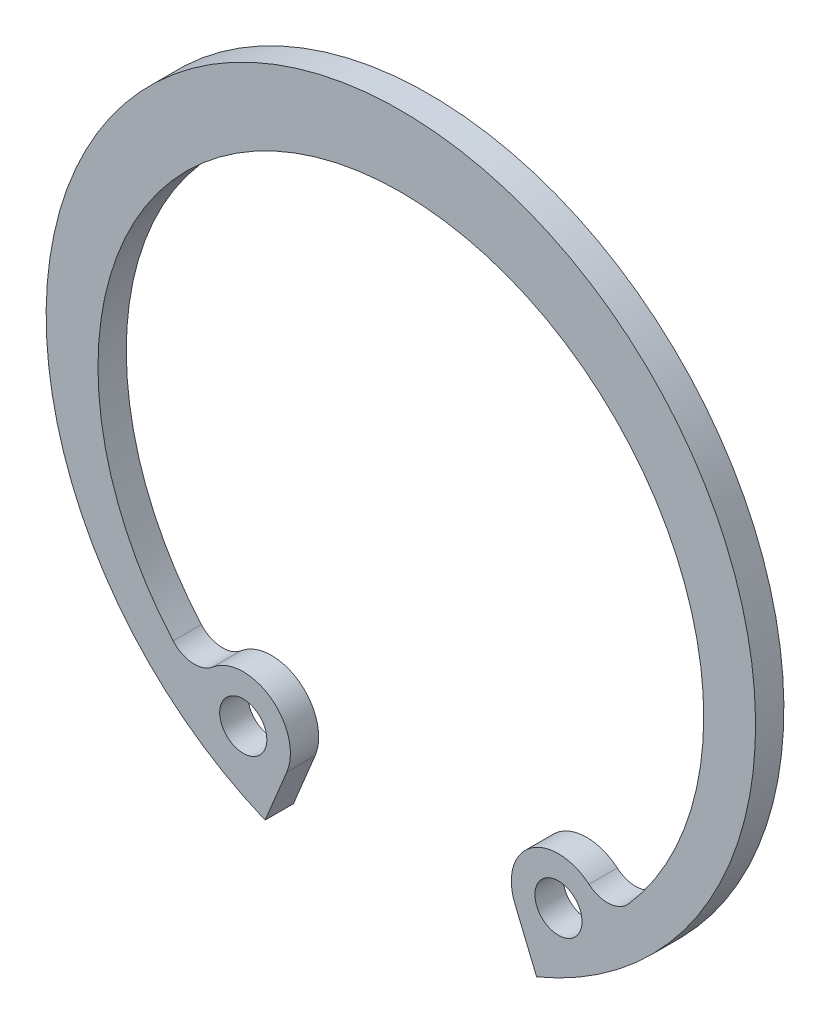
SolidWorks part; units mm, degrees
ref_plane "Front" through (0, 0, 0) normal (0, 0, 1) x (1, 0, 0)
ref_plane "Top" through (0, 0, 0) normal (0, 1, 0) x (1, 0, 0)
ref_plane "Right" through (0, 0, 0) normal (1, 0, 0) x (0, 0, -1)
sketch "Sketch1" plane through (0, 0, 0) normal (0, 0, 1) x (1, 0, 0)
  line L0 (0, 0) -> (-4.8382, -11.6804) construction
  line L1 (0, 7.3554) -> (0, -7.1505) construction
  line L2 (4.8382, -11.6804) -> (5.7594, -13.9044)
  line L4 (-4.8382, -11.6804) -> (-5.7594, -13.9044)
  arc A0 (5.7594, -13.9044) -> (-5.7594, -13.9044) centre (0, 0) ccw
  arc A1 (9.6634, -9.27) -> (-9.6634, -9.27) centre (0, -0.8) ccw
  arc A2 (-4.8382, -11.6804) -> (-7.9828, -9.3925) centre (-6.6859, -10.915) ccw
  arc A3 (-9.6634, -9.27) -> (-7.9828, -9.3925) centre (-8.761, -8.479) ccw
  circle A4 centre (6.6859, -10.915) radius 1
  arc A5 (9.6634, -9.27) -> (7.9828, -9.3925) centre (8.761, -8.479) cw
  arc A6 (-12.8, 0) -> (12.8, 0) centre (0, 0) ccw construction
  circle A7 centre (-6.6859, -10.915) radius 1
  arc A8 (4.8382, -11.6804) -> (7.9828, -9.3925) centre (6.6859, -10.915) cw
  dimension "D" = 30.1
  dimension "d0" = 25.7
  dimension "R1" = 2
  dimension "R2" = 1.2
  dimension "d1" = 2
  dimension "R" = 12.8
  dimension "C" = 0.8
  dimension "Angle" = 45
extrude "Body" add sketch "Sketch1" against normal blind 1.2
